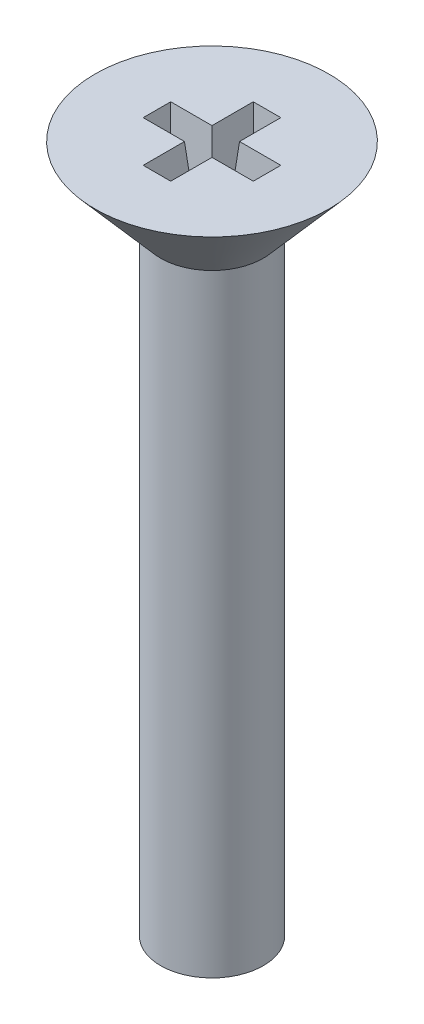
SolidWorks part; units mm, degrees
ref_plane "Front Plane" through (0, 0, 0) normal (0, 0, 1) x (1, 0, 0)
ref_plane "Top Plane" through (0, 0, 0) normal (0, 1, 0) x (1, 0, 0)
ref_plane "Right Plane" through (0, 0, 0) normal (1, 0, 0) x (0, 0, -1)
sketch "Sketch1" plane through (0, 0, 0) normal (0, 0, 1) x (1, 0, 0)
  line L1 (1.4224, 0) -> (3.2385, 2.0892)
  line L5 (3.2385, 2.0892) -> (0, 2.0892)
  line L6 (0, 2.0892) -> (0, 0)
  line L7 (0, 0) -> (0, -16.9608)
  line L8 (0, -16.9608) -> (1.4224, -16.9608)
  line L9 (1.4224, -16.9608) -> (1.4224, 0)
  line L11 (1.4224, 0) -> (0, 0) construction
  dimension "D1" = 19.05
  dimension "D2" = 1.4224
  dimension "D3" = 41
  dimension "D4" = 3.2385
revolve "Revolve1" add sketch "Sketch1" angle 360 about L7
sketch "Sketch2" plane through (0, 2.0892, 0) normal (0, 1, 0) x (1, 0, 0)
  line L0 (-0.381, 1.524) -> (0.381, 1.524)
  line L1 (0.381, 1.524) -> (0.381, 0.381)
  line L2 (0.381, 0.381) -> (1.524, 0.381)
  line L3 (1.524, 0.381) -> (1.524, -0.381)
  line L4 (1.524, -0.381) -> (0.381, -0.381)
  line L5 (0.381, -0.381) -> (0.381, -1.524)
  line L6 (0.381, -1.524) -> (-0.381, -1.524)
  line L7 (-0.381, -1.524) -> (-0.381, -0.381)
  line L8 (-0.381, -0.381) -> (-1.524, -0.381)
  line L9 (-1.524, -0.381) -> (-1.524, 0.381)
  line L10 (-1.524, 0.381) -> (-0.381, 0.381)
  line L11 (-0.381, 0.381) -> (-0.381, 1.524)
  line L12 (0, 1.524) -> (0, 0) construction
  line L13 (0, 0) -> (1.524, 0) construction
  line L15 (0, -1.524) -> (0, 0) construction
  line L16 (-1.524, 0) -> (0, 0) construction
  dimension "D1" = 0.762
  dimension "D2" = 1.524
extrude "Cut-Extrude1" cut sketch "Sketch2" against normal blind 2.159 draft 5
